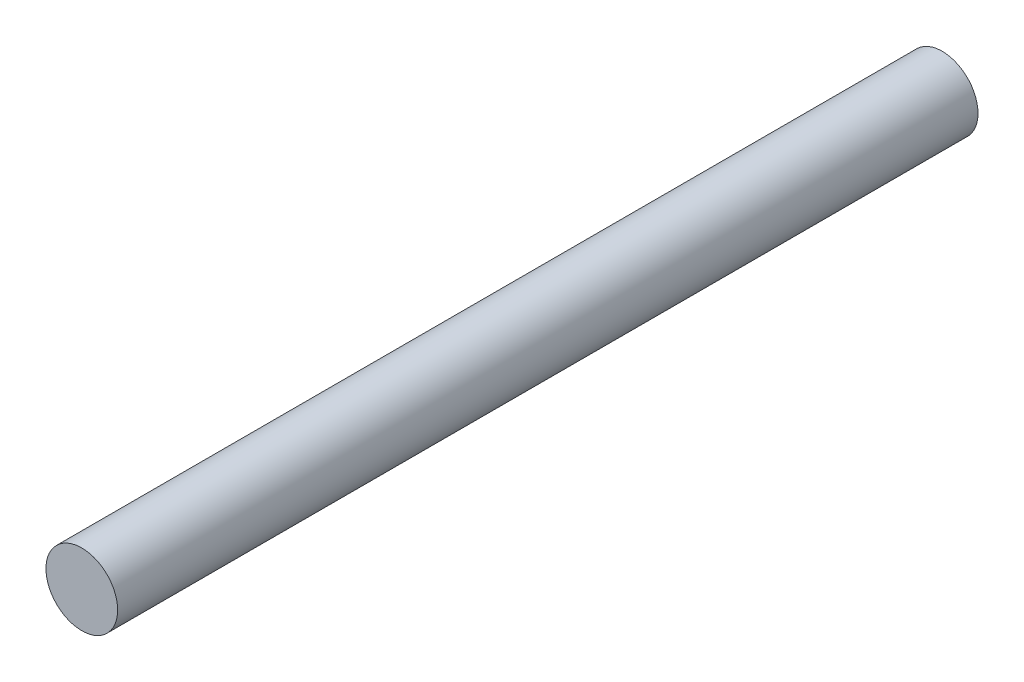
SolidWorks part; units mm, degrees
ref_plane "前视基准面" through (0, 0, 0) normal (0, 0, 1) x (1, 0, 0)
ref_plane "上视基准面" through (0, 0, 0) normal (0, 1, 0) x (1, 0, 0)
ref_plane "右视基准面" through (0, 0, 0) normal (1, 0, 0) x (0, 0, -1)
sketch "草图1" plane through (0, 0, 0) normal (0, 0, 1) x (1, 0, 0)
  circle A0 centre (0, 0) radius 2.5
  dimension "D1" = 5
extrude "拉伸1" add sketch "草图1" along normal blind 60
